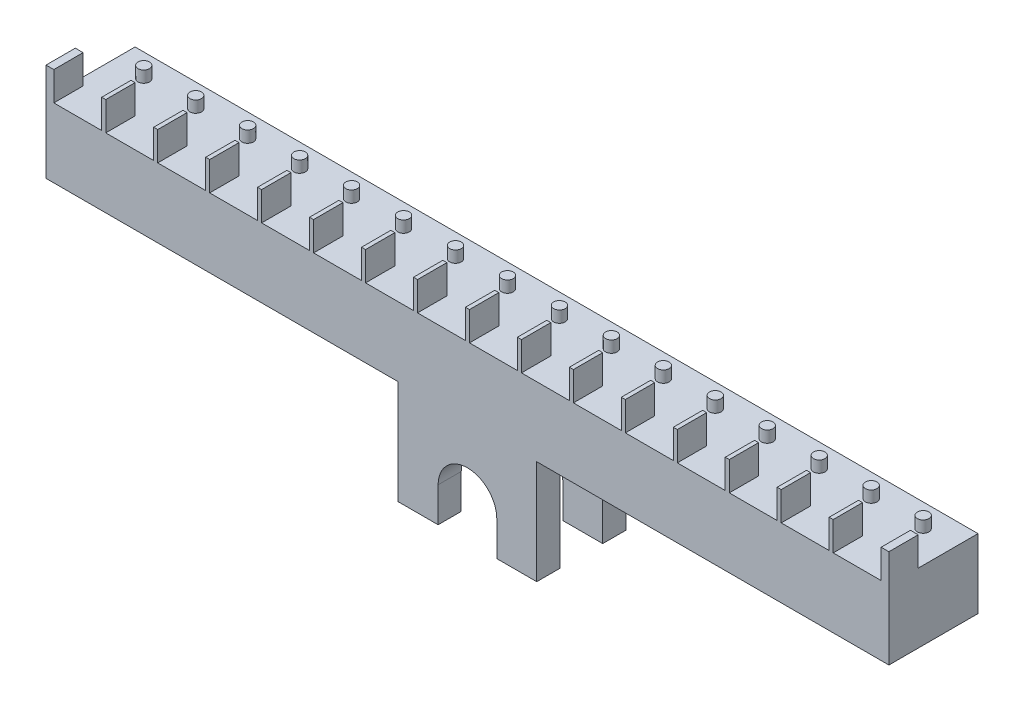
SolidWorks part; units mm, degrees
material "6061-T6 (SS)"
ref_plane "Front" through (0, 0, 0) normal (0, 0, 1) x (1, 0, 0)
ref_plane "Top" through (0, 0, 0) normal (0, 1, 0) x (1, 0, 0)
ref_plane "Right" through (0, 0, 0) normal (1, 0, 0) x (0, 0, -1)
sketch "Sketch1" plane through (0, 0, 0) normal (0, 1, 0) x (1, 0, 0)
  line L1 (-36.5, -5.715) -> (36.5, -5.715)
  line L2 (-36.5, -5.715) -> (-36.5, 2)
  line L3 (-36.5, 2) -> (36.5, 2)
  line L4 (36.5, -5.715) -> (36.5, 2)
  point P9 (0, -5.715)
  dimension "D1" = 7.715
  dimension "D2" = 73
  dimension "D3" = 2
extrude "Boss-Extrude1" add sketch "Sketch1" along normal blind 6
sketch "Sketch2" plane through (0, 6, 0) normal (0, 1, 0) x (1, 0, 0)
  line L0 (0, 5) -> (0, -49995) construction
  line L1 (36.5, 2) -> (-36.5, 2) construction
  line L2 (0, 0) -> (50000, 0) construction
  line L4 (2.25, 0) -> (6.75, 0) construction
  line L5 (-2.25, 0) -> (-6.75, 0) construction
  circle A0 centre (2.25, 0) radius 0.5
  circle A1 centre (6.75, 0) radius 0.5
  circle A2 centre (11.25, 0) radius 0.5
  circle A3 centre (15.75, 0) radius 0.5
  circle A4 centre (20.25, 0) radius 0.5
  circle A5 centre (24.75, 0) radius 0.5
  circle A6 centre (29.25, 0) radius 0.5
  circle A7 centre (33.75, 0) radius 0.5
  circle A8 centre (-33.75, 0) radius 0.5
  circle A9 centre (-29.25, 0) radius 0.5
  circle A10 centre (-24.75, 0) radius 0.5
  circle A11 centre (-20.25, 0) radius 0.5
  circle A12 centre (-15.75, 0) radius 0.5
  circle A13 centre (-11.25, 0) radius 0.5
  circle A14 centre (-6.75, 0) radius 0.5
  circle A15 centre (-2.25, 0) radius 0.5
  point P4 (0, 2)
  dimension "D1" = 1
  dimension "D2" = 2.25
  dimension "D4" = 4.5
  dimension "D3" = 8
extrude "Boss-Extrude2" add sketch "Sketch2" along normal blind 1
sketch "Sketch3" plane through (0, 6, 0) normal (0, 1, 0) x (1, 0, 0)
  line L0 (0, 5) -> (0, -49995) construction
  line L1 (36.5, 2) -> (-36.5, 2) construction
  line L2 (4.325, -3.175) -> (4.675, -3.175)
  line L3 (-0.175, -3.175) -> (0.175, -3.175)
  line L4 (-0.175, -3.175) -> (-0.175, -5.715)
  line L5 (-0.175, -5.715) -> (0.175, -5.715)
  line L6 (0.175, -3.175) -> (0.175, -5.715)
  line L7 (-36.5, -5.715) -> (36.5, -5.715) construction
  line L8 (4.325, -3.175) -> (4.325, -5.715)
  line L9 (4.325, -5.715) -> (4.675, -5.715)
  line L10 (4.675, -3.175) -> (4.675, -5.715)
  line L11 (8.825, -3.175) -> (9.175, -3.175)
  line L12 (8.825, -3.175) -> (8.825, -5.715)
  line L13 (8.825, -5.715) -> (9.175, -5.715)
  line L14 (9.175, -3.175) -> (9.175, -5.715)
  line L16 (13.325, -3.175) -> (13.325, -5.715)
  line L17 (13.325, -5.715) -> (13.675, -5.715)
  line L18 (13.675, -3.175) -> (13.675, -5.715)
  line L20 (17.825, -3.175) -> (17.825, -5.715)
  line L21 (17.825, -5.715) -> (18.175, -5.715)
  line L22 (18.175, -3.175) -> (18.175, -5.715)
  line L23 (22.325, -3.175) -> (22.675, -3.175)
  line L24 (22.325, -3.175) -> (22.325, -5.715)
  line L25 (22.325, -5.715) -> (22.675, -5.715)
  line L26 (22.675, -3.175) -> (22.675, -5.715)
  line L27 (26.825, -3.175) -> (27.175, -3.175)
  line L28 (26.825, -3.175) -> (26.825, -5.715)
  line L29 (26.825, -5.715) -> (27.175, -5.715)
  line L30 (27.175, -3.175) -> (27.175, -5.715)
  line L31 (31.325, -3.175) -> (31.675, -3.175)
  line L32 (31.325, -3.175) -> (31.325, -5.715)
  line L33 (31.325, -5.715) -> (31.675, -5.715)
  line L34 (31.675, -3.175) -> (31.675, -5.715)
  line L35 (35.825, -3.175) -> (36.175, -3.175)
  line L36 (35.825, -3.175) -> (35.825, -5.715)
  line L37 (35.825, -5.715) -> (36.175, -5.715)
  line L38 (36.175, -3.175) -> (36.175, -5.715)
  line L39 (-0.175, -3.175) -> (4.325, -3.175) construction
  line L40 (-4.675, -3.175) -> (-4.325, -3.175)
  line L41 (-4.675, -3.175) -> (-4.675, -5.715)
  line L42 (-4.675, -5.715) -> (-4.325, -5.715)
  line L43 (-4.325, -3.175) -> (-4.325, -5.715)
  line L44 (-9.175, -3.175) -> (-8.825, -3.175)
  line L45 (-9.175, -3.175) -> (-9.175, -5.715)
  line L46 (-9.175, -5.715) -> (-8.825, -5.715)
  line L47 (-8.825, -3.175) -> (-8.825, -5.715)
  line L48 (-13.675, -3.175) -> (-13.325, -3.175)
  line L49 (-13.675, -3.175) -> (-13.675, -5.715)
  line L50 (-13.675, -5.715) -> (-13.325, -5.715)
  line L51 (-13.325, -3.175) -> (-13.325, -5.715)
  line L52 (-18.175, -3.175) -> (-17.825, -3.175)
  line L53 (-18.175, -3.175) -> (-18.175, -5.715)
  line L54 (-18.175, -5.715) -> (-17.825, -5.715)
  line L55 (-17.825, -3.175) -> (-17.825, -5.715)
  line L56 (-22.675, -3.175) -> (-22.325, -3.175)
  line L57 (-22.675, -3.175) -> (-22.675, -5.715)
  line L58 (-22.675, -5.715) -> (-22.325, -5.715)
  line L59 (-22.325, -3.175) -> (-22.325, -5.715)
  line L60 (-27.175, -3.175) -> (-26.825, -3.175)
  line L61 (-27.175, -3.175) -> (-27.175, -5.715)
  line L62 (-27.175, -5.715) -> (-26.825, -5.715)
  line L63 (-26.825, -3.175) -> (-26.825, -5.715)
  line L64 (-31.675, -3.175) -> (-31.325, -3.175)
  line L65 (-31.675, -3.175) -> (-31.675, -5.715)
  line L66 (-31.675, -5.715) -> (-31.325, -5.715)
  line L67 (-31.325, -3.175) -> (-31.325, -5.715)
  line L68 (-36.175, -3.175) -> (-35.825, -3.175)
  line L69 (-36.175, -3.175) -> (-36.175, -5.715)
  line L70 (-36.175, -5.715) -> (-35.825, -5.715)
  line L71 (-35.825, -3.175) -> (-35.825, -5.715)
  line L72 (-0.175, -3.175) -> (-4.675, -3.175) construction
  line L73 (13.325, -3.175) -> (13.675, -3.175) [skipped]
  line L74 (17.825, -3.175) -> (18.175, -3.175) [skipped]
  line L75 (13.325, -3.175) -> (13.675, -3.175)
  line L76 (17.825, -3.175) -> (18.175, -3.175)
  line L77 (-2.25, 0) -> (-4.325, -3.175) construction
  circle A0 centre (-3.4243, -1.7968) radius 1.6465 construction
  circle A3 centre (-2.25, 0) radius 0.5 construction
  circle A5 centre (-2.25, 0) radius 3.4885 construction
  point P4 (0, 2)
  dimension "D7" = 6.977
  dimension "D8" = 3.2929
  dimension "D1" = 2.54
  dimension "D2" = 0.35
  dimension "D3" = 9
  dimension "D4" = 4.5
  dimension "D6" = 4.5
  dimension "D5" = 9
extrude "Boss-Extrude3" add sketch "Sketch3" along normal offset from surface (2.5 mm away) 8.5 up to face at (0, 0, 1.8575)
sketch "Sketch4" plane through (0, 0, 3.175) normal (0, 0, 1) x (1, 0, 0)
  line L0 (-36.175, 8.5) -> (-35.825, 8.5) construction
  line L1 (-36.175, 6) -> (-36.5, 6)
  line L2 (-36.175, 6) -> (-36.175, 8.5)
  line L3 (-36.175, 8.5) -> (-36.5, 8.5)
  line L4 (-36.5, 6) -> (-36.5, 8.5)
  line L5 (-36.5, 6) -> (-36.5, 0) construction
  line L7 (36.175, 8.5) -> (36.5, 8.5)
  line L8 (36.175, 8.5) -> (36.175, 6)
  line L9 (36.175, 6) -> (36.5, 6)
  line L10 (36.5, 8.5) -> (36.5, 6)
extrude "Boss-Extrude4" add sketch "Sketch4" along normal up to surface (2.54 mm away) up to face at (0, 7.0139, 5.715)
sketch "Sketch12" plane through (0, 0, 0) normal (0, 0, 1) x (1, 0, 0)
  line L0 (0, -1.9017) -> (0, -7.24) construction
  line L1 (-2.54, -6) -> (-2.54, -9)
  line L2 (-6, 0) -> (6, 0)
  line L3 (-6, 0) -> (-6, -9)
  line L4 (-6, -9) -> (-2.54, -9)
  line L5 (6, 0) -> (6, -9)
  line L6 (2.54, -6) -> (2.54, -9)
  line L7 (2.54, -9) -> (6, -9)
  line L8 (-36.5, 0) -> (36.5, 0) construction
  arc A0 (2.54, -6) -> (-2.54, -6) centre (0, -6) ccw
  point P6 (0, 0)
  dimension "D3" = 5.08
  dimension "D1" = 12
  dimension "D2" = 9
  dimension "D4" = 6
extrude "Boss-Extrude12" add sketch "Sketch12" along normal through all and the other way through all
sketch "Sketch13" plane through (0, 0, 0) normal (0, -1, 0) x (1, 0, 0)
  line L0 (-6, 5.715) -> (-6, -2) construction
  line L1 (-6, 3.715) -> (6, 3.715)
  line L2 (-6, 3.715) -> (-6, 0)
  line L3 (-6, 0) -> (6, 0)
  line L4 (6, 3.715) -> (6, 0)
  line L5 (6, 5.715) -> (6, -2) construction
  line L6 (-6, 5.715) -> (-2.54, 5.715) construction
  line L7 (-6, -2) -> (-2.54, -2) construction
  dimension "D1" = 2
  dimension "D2" = 2
extrude "Cut-Extrude1" cut sketch "Sketch13" along normal through all
